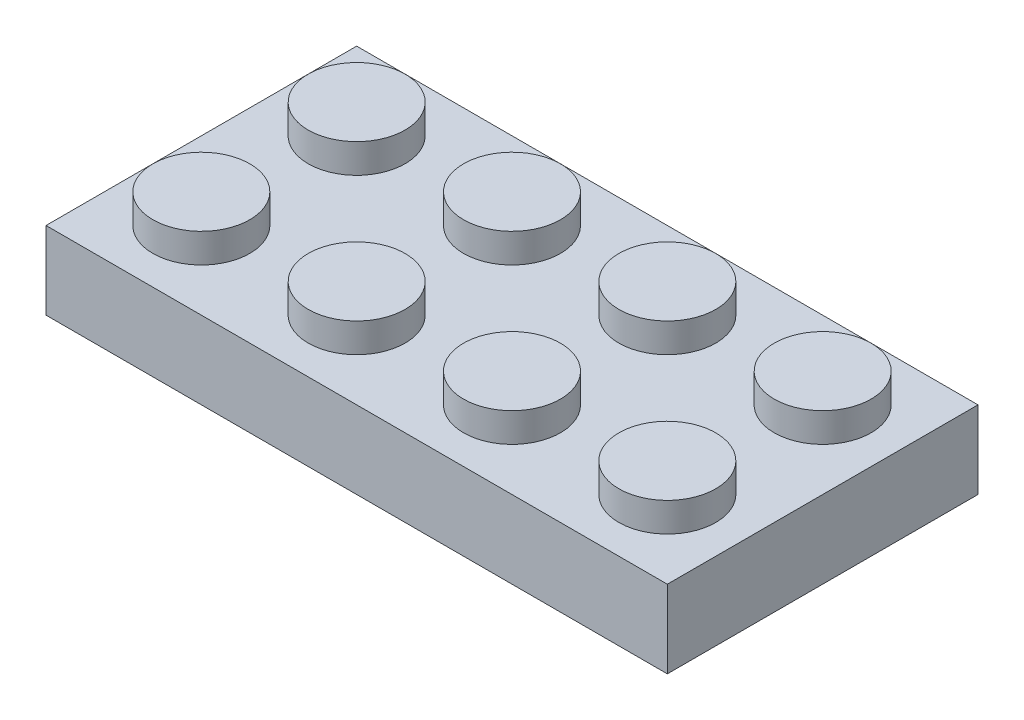
SolidWorks part; units mm, degrees
material "Oak"
ref_plane "Front Plane" through (0, 0, 0) normal (0, 0, 1) x (1, 0, 0)
ref_plane "Top Plane" through (0, 0, 0) normal (0, 1, 0) x (1, 0, 0)
ref_plane "Right Plane" through (0, 0, 0) normal (1, 0, 0) x (0, 0, -1)
sketch "Sketch1" plane through (0, 0, 0) normal (0, 1, 0) x (1, 0, 0)
  line L1 (12.7, -6.35) -> (-12.7, -6.35)
  line L2 (12.7, -6.35) -> (12.7, 6.35)
  line L3 (12.7, 6.35) -> (-12.7, 6.35)
  line L4 (-12.7, -6.35) -> (-12.7, 6.35)
  line L5 (12.7, -6.35) -> (-12.7, 6.35) construction
  line L6 (12.7, 6.35) -> (-12.7, -6.35) construction
  point P0 (0, 0)
  dimension "D1" = 12.7
  dimension "D2" = 25.4
extrude "Boss-Extrude1" add sketch "Sketch1" along normal blind 3.175
sketch "Sketch2" plane through (0, 3.175, 0) normal (0, 1, 0) x (1, 0, 0)
  line L0 (12.7, 6.35) -> (-12.7, 6.35) construction
  line L1 (-12.7, 6.35) -> (-12.7, -6.35) construction
  circle A0 centre (-9.525, 3.175) radius 1.9812
  dimension "D1" = 3.9624
  dimension "D2" = 3.175
  dimension "D3" = 3.175
extrude "Boss-Extrude2" add sketch "Sketch2" along normal blind 1.1938
pattern_linear "LPattern1" count 4 spacing 6.35 along (1, 0, 0) count 2 spacing 6.35 along (0, 0, 1) of "Boss-Extrude2"
shell "Shell2" thickness 1.1938
sketch "Sketch3" plane through (0, 1.9812, 0) normal (0, -1, 0) x (1, 0, 0)
  line L0 (12.7, 6.35) -> (12.7, -6.35) construction
  line L1 (-12.7, 6.35) -> (12.7, 6.35) construction
  circle A0 centre (6.35, 0) radius 2.5019
  circle A1 centre (6.35, 0) radius 1.9812
  dimension "D1" = 5.0038
  dimension "D2" = 3.9624
  dimension "D3" = 6.35
  dimension "D4" = 6.35
extrude "Boss-Extrude3" add sketch "Sketch3" along normal up to surface (1.9812 mm away) up to face at (0, 0, 0)
pattern_linear "LPattern2" count 3 spacing 6.35 along (-1, 0, 0) of "Boss-Extrude3"
